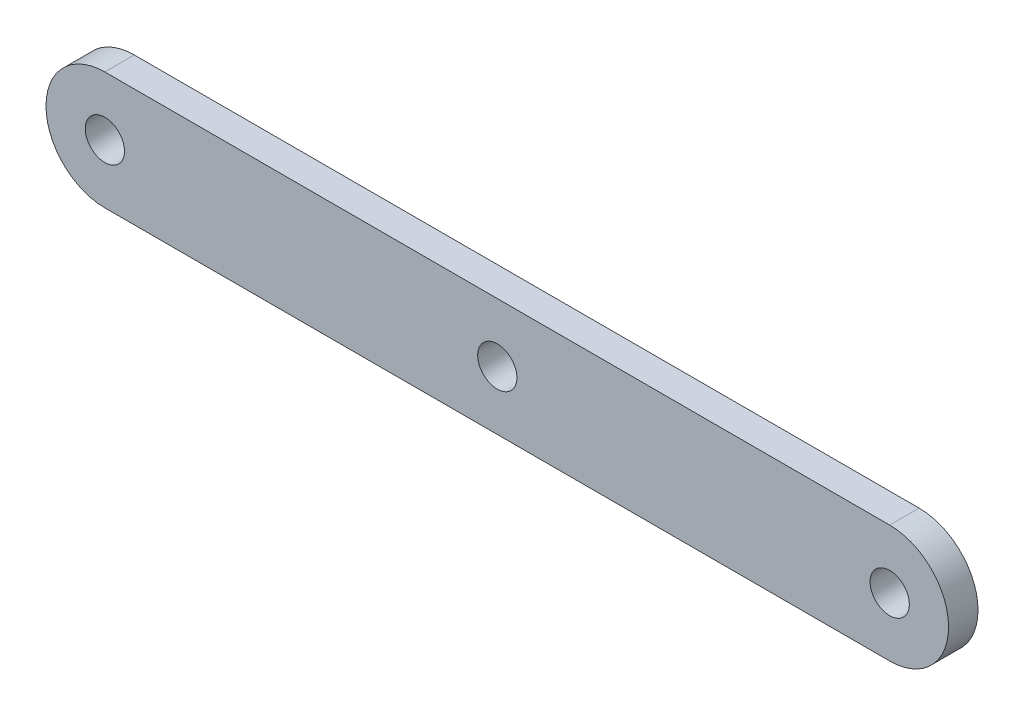
SolidWorks part; units mm, degrees
ref_plane "Front Plane" through (0, 0, 0) normal (0, 0, 1) x (1, 0, 0)
ref_plane "Top Plane" through (0, 0, 0) normal (0, 1, 0) x (1, 0, 0)
ref_plane "Right Plane" through (0, 0, 0) normal (1, 0, 0) x (0, 0, -1)
sketch "Sketch1" plane through (0, 0, 0) normal (0, 0, 1) x (1, 0, 0)
  line L0 (-35.3127, 0) -> (44.6873, 0) construction
  line L1 (-35.3127, 6) -> (44.6873, 6)
  line L2 (-35.3127, -6) -> (44.6873, -6)
  arc A0 (-35.3127, 6) -> (-35.3127, -6) centre (-35.3127, 0) ccw
  arc A1 (44.6873, -6) -> (44.6873, 6) centre (44.6873, 0) ccw
  circle A2 centre (-35.3127, 0) radius 2
  circle A3 centre (44.6873, 0) radius 2
  circle A4 centre (4.6873, 0) radius 2
  point P3 (4.6873, 0)
  dimension "D3" = 4
  dimension "D4" = 4
  dimension "D1" = 80
  dimension "D2" = 12
extrude "Boss-Extrude3" add sketch "Sketch1" along normal blind 3
